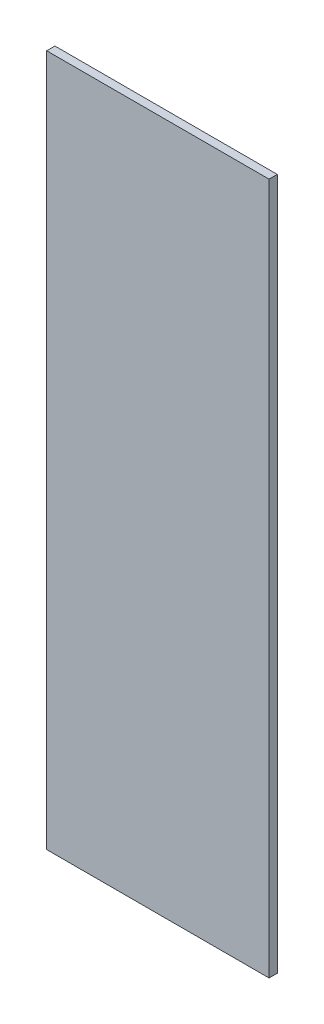
SolidWorks part; units mm, degrees
ref_plane "Front" through (0, 0, 0) normal (0, 0, 1) x (1, 0, 0)
ref_plane "Top" through (0, 0, 0) normal (0, 1, 0) x (1, 0, 0)
ref_plane "Right" through (0, 0, 0) normal (1, 0, 0) x (0, 0, -1)
sketch "Sketch1" plane through (0, 0, 0) normal (0, 0, 1) x (1, 0, 0)
  line L5 (-171.45, -533.4) -> (171.45, -533.4)
  line L6 (-171.45, -533.4) -> (-171.45, 533.4)
  line L7 (-171.45, 533.4) -> (171.45, 533.4)
  line L8 (171.45, -533.4) -> (171.45, 533.4)
  line L9 (-171.45, -533.4) -> (171.45, 533.4) construction
  line L10 (-171.45, 533.4) -> (171.45, -533.4) construction
  point P4 (0, 0)
  dimension "D1" = 342.9
  dimension "D2" = 1066.8
extrude "Boss-Extrude1" add sketch "Sketch1" along normal blind 12.7
